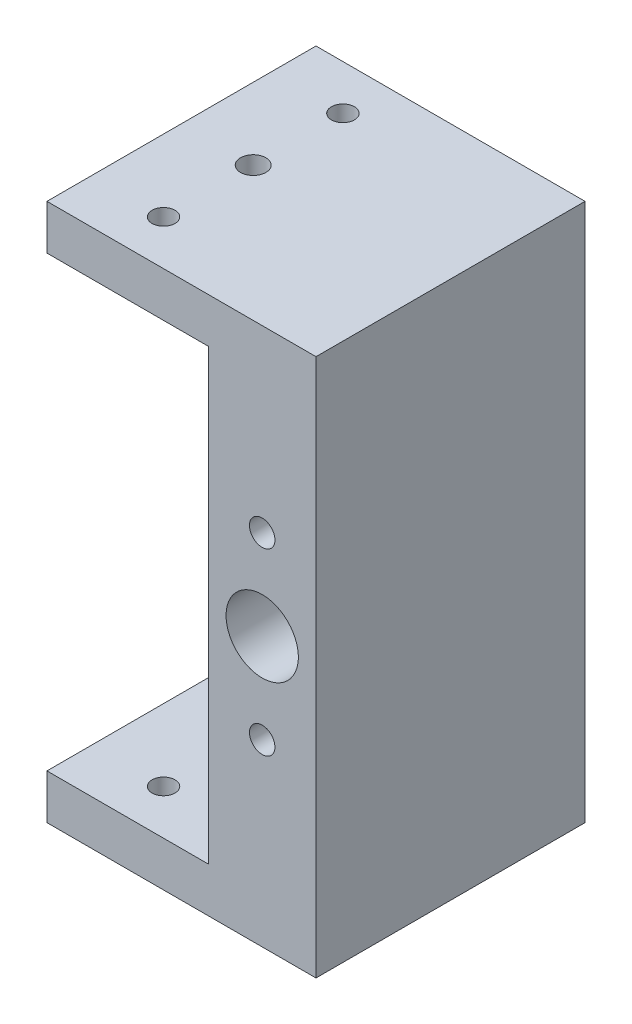
SolidWorks part; units mm, degrees
material "ABS"
ref_plane "Front Plane" through (0, 0, 0) normal (0, 0, 1) x (1, 0, 0)
ref_plane "Top Plane" through (0, 0, 0) normal (0, 1, 0) x (1, 0, 0)
ref_plane "Right Plane" through (0, 0, 0) normal (1, 0, 0) x (0, 0, -1)
sketch "Sketch1" plane through (0, 0, 0) normal (0, 0, 1) x (1, 0, 0)
  line L1 (-19.05, -38.1) -> (19.05, -38.1)
  line L2 (-19.05, -38.1) -> (-19.05, 38.1)
  line L3 (-19.05, 38.1) -> (19.05, 38.1)
  line L4 (19.05, -38.1) -> (19.05, 38.1)
  line L5 (-19.05, -38.1) -> (19.05, 38.1) construction
  line L6 (-19.05, 38.1) -> (19.05, -38.1) construction
  point P0 (0, 0)
  dimension "D1" = 76.2
  dimension "D2" = 38.1
extrude "Boss-Extrude1" add sketch "Sketch1" along normal blind 38.1
sketch "Sketch2" plane through (0, 0, 0) normal (0, 0, -1) x (-1, 0, 0)
  line L0 (19.05, 38.1) -> (19.05, -38.1) construction
  line L1 (19.05, 31.75) -> (-3.81, 31.75)
  line L2 (19.05, 31.75) -> (19.05, -31.75)
  line L3 (19.05, -31.75) -> (-3.81, -31.75)
  line L4 (-3.81, 31.75) -> (-3.81, -31.75)
  line L5 (-19.05, 38.1) -> (19.05, 38.1) construction
  line L6 (19.05, -38.1) -> (-19.05, -38.1) construction
  dimension "D1" = 6.35
  dimension "D2" = 6.35
  dimension "D3" = 22.86
extrude "Cut-Extrude1" cut sketch "Sketch2" against normal blind 38.1
sketch "Sketch3" plane through (0, 0, 0) normal (0, 0, -1) x (-1, 0, 0)
  line L0 (-19.05, 38.1) -> (19.05, 38.1) construction
  line L2 (-19.05, -38.1) -> (-19.05, 38.1) construction
  circle A0 centre (-11.43, 0) radius 5.1181
  circle A1 centre (-11.43, -12.7) radius 1.8034
  circle A2 centre (-11.43, 12.7) radius 1.8034
  dimension "D1" = 3.6068
  dimension "D2" = 3.6068
  dimension "D3" = 10.2362
  dimension "D4" = 12.7
  dimension "D5" = 12.7
  dimension "D6" = 38.1
  dimension "D7" = 7.62
extrude "Cut-Extrude2" cut sketch "Sketch3" against normal blind 38.1
sketch "Sketch4" plane through (0, -38.1, 0) normal (0, -1, 0) x (-1, 0, 0)
  line L0 (19.05, 0) -> (-19.05, 0) construction
  line L1 (19.05, -38.1) -> (19.05, 0) construction
  circle A0 centre (8.89, -6.35) radius 1.6256
  circle A1 centre (8.89, -19.05) radius 1.8034
  circle A2 centre (8.89, -31.75) radius 1.6256
  dimension "D1" = 3.2512
  dimension "D2" = 3.2512
  dimension "D3" = 3.6068
  dimension "D4" = 19.05
  dimension "D5" = 12.7
  dimension "D6" = 12.7
  dimension "D7" = 10.16
extrude "Cut-Extrude3" cut sketch "Sketch4" against normal blind 76.2
